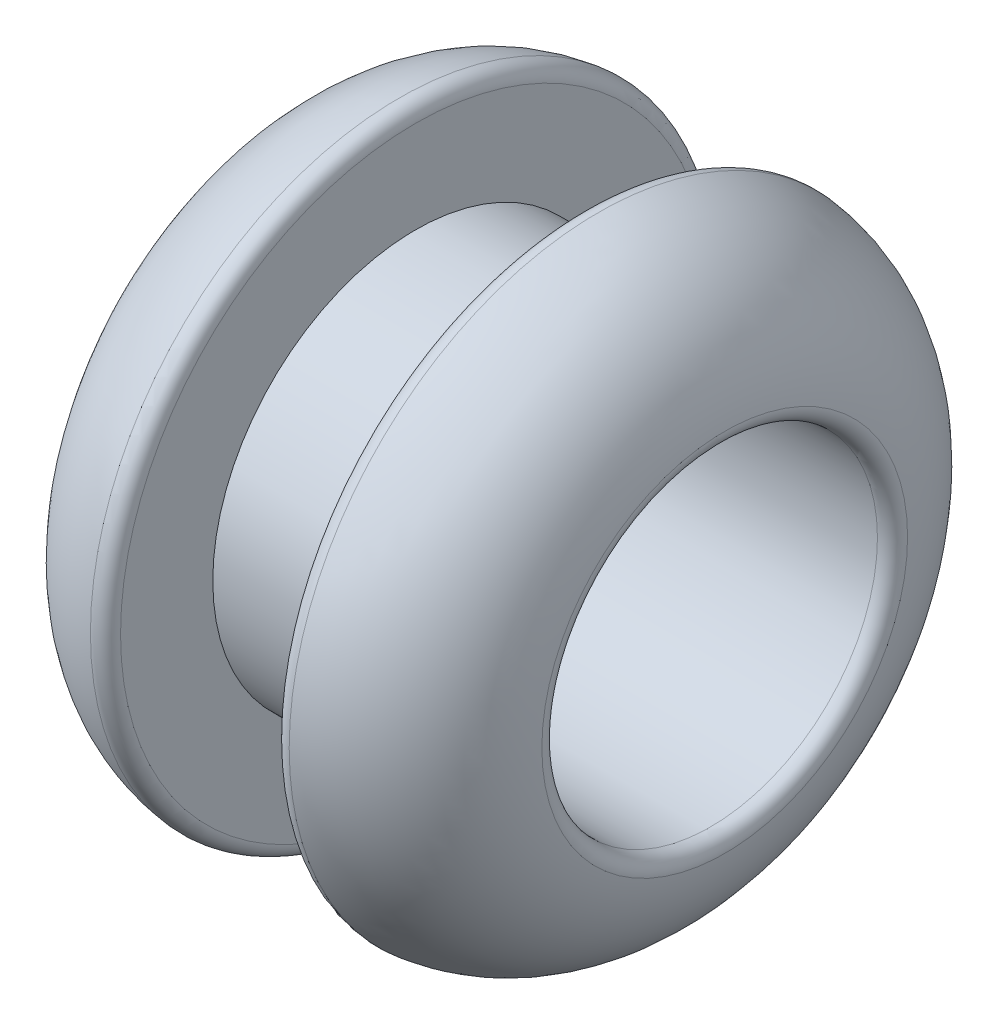
SolidWorks part; units mm, degrees
ref_plane "Front Plane" through (0, 0, 0) normal (0, 0, 1) x (1, 0, 0)
ref_plane "Top Plane" through (0, 0, 0) normal (0, 1, 0) x (1, 0, 0)
ref_plane "Right Plane" through (0, 0, 0) normal (1, 0, 0) x (0, 0, -1)
sketch "Sketch2" plane through (0, 0, 0) normal (0, 1, 0) x (1, 0, 0)
  line L0 (0, 0) -> (-4.75, 0)
  line L6 (-3.25, 1.5) -> (-3.25, 0.375)
  line L7 (-3.25, 0.375) -> (-1.5, 0.375)
  line L8 (-1.5, 0.375) -> (-1.5, 1.5)
  line L9 (-6.636, -1.75) -> (2.8786, -1.75)
  arc A0 (-4.75, 0) -> (-3.25, 1.5) centre (-3.25, 0) cw
  arc A1 (0, 0) -> (-1.5, 1.5) centre (-1.5, 0) ccw
  dimension "D1" = 1.75
  dimension "D2" = 4.75
  dimension "D3" = 1.125
  dimension "D4" = 1.75
revolve "Revolve1" add sketch "Sketch2" angle 360 about L9
fillet "Fillet1" radius 0.15 4 edges at (0, 0, 3.5) (-4.75, 0, 3.5) (-3.25, 0, 5) (-1.5, 0, 5)
